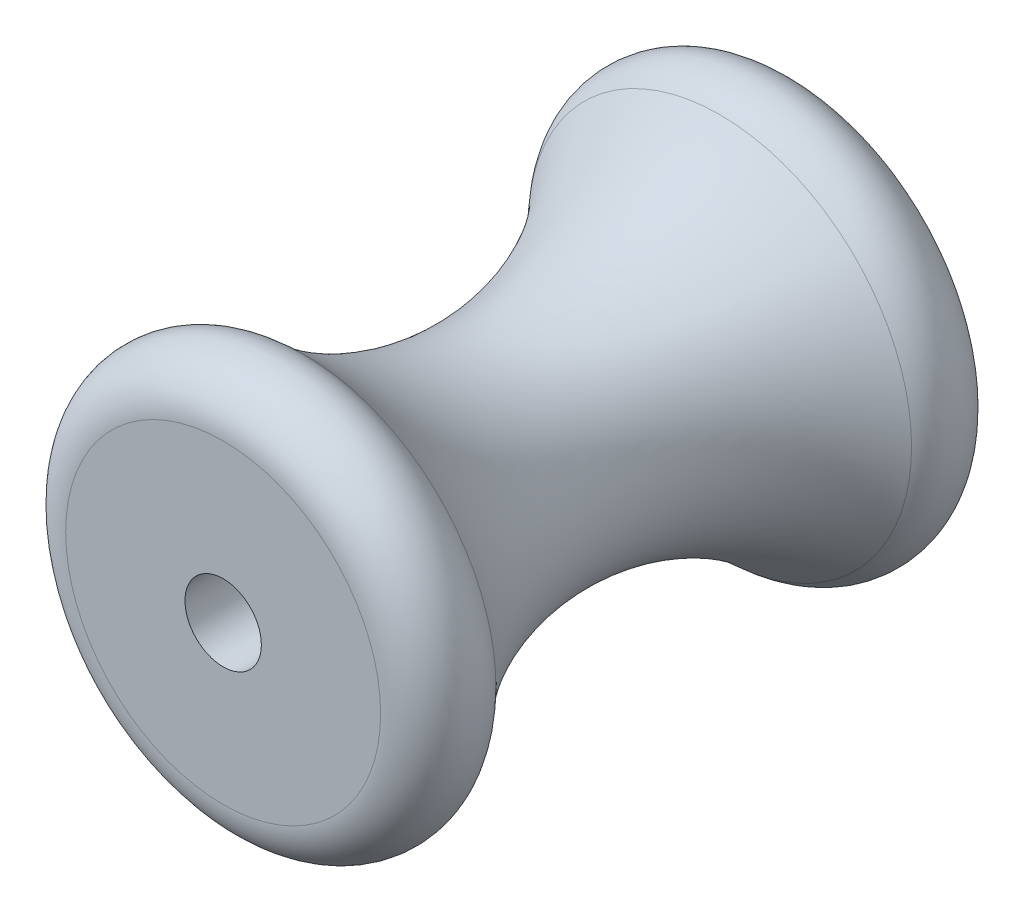
SolidWorks part; units mm, degrees
ref_plane "Front Plane" through (0, 0, 0) normal (0, 0, 1) x (1, 0, 0)
ref_plane "Top Plane" through (0, 0, 0) normal (0, 1, 0) x (1, 0, 0)
ref_plane "Right Plane" through (0, 0, 0) normal (1, 0, 0) x (0, 0, -1)
sketch "Sketch1" plane through (0, 0, 0) normal (1, 0, 0) x (0, 0, -1)
  line L0 (12.5, 0) -> (-12.5, 0) construction
  line L1 (8.0683, 13.3135) -> (18.6863, -18.5845) construction
  line L2 (12.5, 1.6) -> (-12.5, 1.6) construction
  line L3 (-12.5, 19) -> (-12.5, 17.3425) construction
  line L4 (0, 9.4558) -> (0, -9.4558) construction
  line L5 (12.5, 1.6) -> (12.5, 17) construction
  line L6 (-12.5, 1.6) -> (-12.5, 17) construction
  line L7 (12.1, 1.6) -> (12.1, 13.8631)
  line L8 (-12.1, 1.6) -> (-12.1, 13.8631)
  line L9 (12.1, 1.6) -> (-12.1, 1.6)
  circle A0 centre (0, 17) radius 12.5 construction
  arc A1 (12.1, 13.8631) -> (-12.1, 13.8631) centre (0, 17) cw
  point P2 (0, 0)
  dimension "D1" = 0.8
revolve "Revolve1" add sketch "Sketch1" angle 360 about L0
fillet "Fillet1" radius 2 2 edges at (0, 13.8631, 12.1) (0, 13.8631, -12.1)
